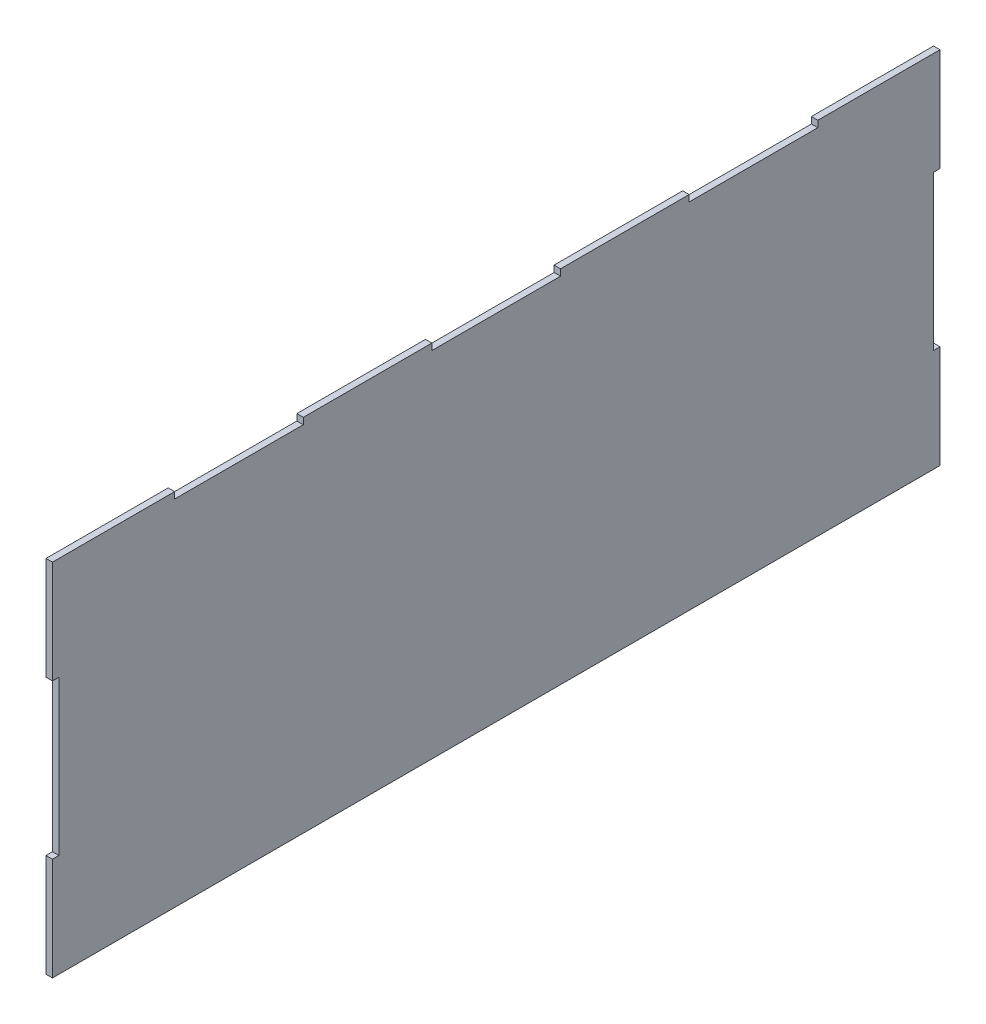
SolidWorks part; units mm, degrees
ref_plane "Ebene vorne" through (0, 0, 0) normal (0, 0, 1) x (1, 0, 0)
ref_plane "Ebene oben" through (0, 0, 0) normal (0, 1, 0) x (1, 0, 0)
ref_plane "Ebene rechts" through (0, 0, 0) normal (1, 0, 0) x (0, 0, -1)
sketch "Skizze1" plane through (0, 0, 0) normal (1, 0, 0) x (0, 0, -1)
  line L1 (-340, 140) -> (340, 140)
  line L2 (-340, 140) -> (-340, -140)
  line L3 (-340, -140) -> (340, -140)
  line L4 (340, 140) -> (340, -140)
  line L5 (-340, 140) -> (340, -140) construction
  line L6 (-340, -140) -> (340, 140) construction
  point P0 (0, 0)
  dimension "D1" = 680
  dimension "D2" = 280
extrude "Aufsatz-Linear austragen1" add sketch "Skizze1" along normal blind 5
sketch "Skizze2" plane through (5, 0, 0) normal (1, 0, 0) x (0, 0, -1)
  line L0 (0, -140) -> (0, 140) construction
  line L1 (-340, 140) -> (-345, 140)
  line L2 (-340, 140) -> (-340, 60)
  line L3 (-340, 60) -> (-345, 60)
  line L4 (-345, 140) -> (-345, 60)
  line L5 (-340, -140) -> (-345, -140)
  line L6 (-340, -140) -> (-340, -60)
  line L7 (-340, -60) -> (-345, -60)
  line L8 (-345, -140) -> (-345, -60)
  line L9 (-340, -140) -> (340, -140) construction
  line L10 (340, 140) -> (-340, 140) construction
  line L11 (345, -140) -> (345, -60)
  line L12 (340, -60) -> (345, -60)
  line L13 (340, -140) -> (340, -60)
  line L14 (340, -140) -> (345, -140)
  line L15 (345, 140) -> (345, 60)
  line L16 (340, 60) -> (345, 60)
  line L17 (340, 140) -> (340, 60)
  line L18 (340, 140) -> (345, 140)
  dimension "D1" = 5
  dimension "80" = 80
extrude "Aufsatz-Linear austragen2" add sketch "Skizze2" against normal up to surface (5 mm away) up to face at (0, 0, 0)
sketch "Skizze3" plane through (5, 0, 0) normal (1, 0, 0) x (0, 0, -1)
  line L0 (0, 140) -> (0, -140) construction
  line L1 (345, 140) -> (-345, 140) construction
  line L2 (-345, -140) -> (345, -140) construction
  line L15 (-340, 0) -> (340, 0) construction
  line L16 (-340, 60) -> (-340, -60) construction
  line L17 (340, -60) -> (340, 60) construction
  line L18 (150, 135) -> (250, 135)
  line L19 (150, 135) -> (150, 140)
  line L20 (150, 140) -> (250, 140)
  line L21 (-250, 135) -> (-250, 140)
  line L22 (-150, 140) -> (-250, 140)
  line L23 (-150, 135) -> (-150, 140)
  line L24 (-150, 135) -> (-250, 135)
  line L25 (250, 135) -> (250, 140)
  line L26 (50, 135) -> (50, 140)
  line L27 (-50, 140) -> (50, 140)
  line L28 (-50, 135) -> (-50, 140)
  line L29 (50, 135) -> (-50, 135)
  point P37 (0, 135)
  dimension "D1" = 100
  dimension "D2" = 100
  dimension "D3" = 5
extrude "Schnitt-Linear austragen1" cut sketch "Skizze3" against normal through all
